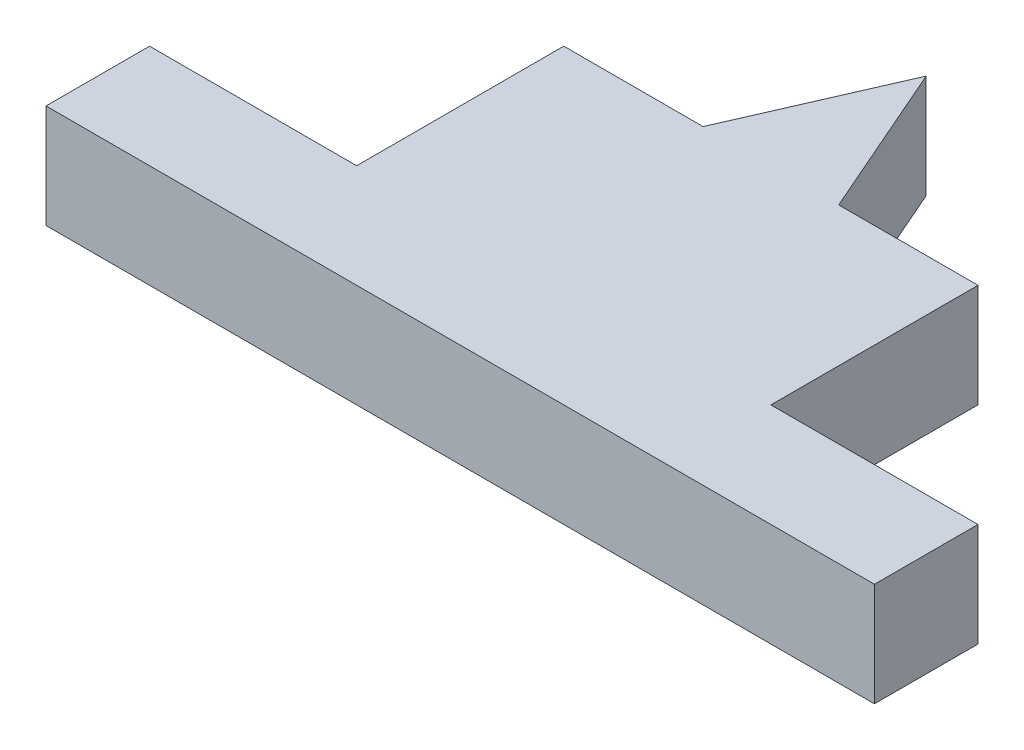
SolidWorks part; units mm, degrees
ref_plane "Front Plane" through (0, 0, 0) normal (0, 0, 1) x (1, 0, 0)
ref_plane "Top Plane" through (0, 0, 0) normal (0, 1, 0) x (1, 0, 0)
ref_plane "Right Plane" through (0, 0, 0) normal (1, 0, 0) x (0, 0, -1)
sketch "Sketch1" plane through (0, 0, 0) normal (0, 1, 0) x (1, 0, 0)
  line L0 (0, 0) -> (0, 11.5486) construction
  line L1 (-12.7, 1.5875) -> (-6.35, 1.5875)
  line L2 (-12.7, 1.5875) -> (-12.7, -1.5875)
  line L3 (-12.7, -1.5875) -> (12.7, -1.5875)
  line L4 (12.7, 1.5875) -> (12.7, -1.5875)
  line L5 (-12.7, 1.5875) -> (12.7, -1.5875) construction
  line L6 (-12.7, -1.5875) -> (12.7, 1.5875) construction
  line L7 (-2.0792, 7.9375) -> (0, 12.7)
  line L8 (0, 12.7) -> (2.0792, 7.9375)
  line L9 (-6.35, 1.5875) -> (-6.35, 7.9375)
  line L10 (6.35, 1.5875) -> (12.7, 1.5875)
  line L11 (-6.35, 7.9375) -> (-2.0792, 7.9375)
  line L12 (6.35, 7.9375) -> (2.0792, 7.9375)
  line L13 (6.35, 1.5875) -> (6.35, 7.9375)
  point P0 (0, 0)
  point P8 (6.35, 1.5875)
  point P9 (-6.35, 1.5875)
  point P10 (0, 12.7)
  point P13 (-6.35, 7.9375)
  dimension "D1" = 3.175
  dimension "D2" = 25.4
  dimension "D3" = 6.35
  dimension "D4" = 6.35
  dimension "D5" = 11.1125
  dimension "D6" = 6.35
extrude "Boss-Extrude1" add sketch "Sketch1" along normal blind 3.175
